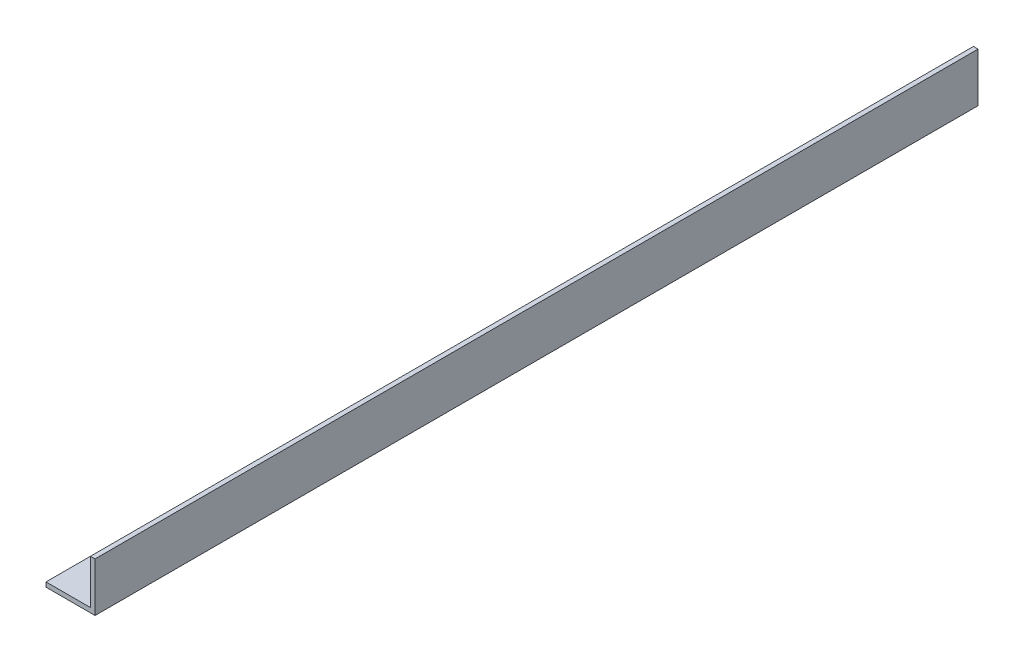
SolidWorks part; units mm, degrees
ref_plane "Front Plane" through (0, 0, 0) normal (0, 0, 1) x (1, 0, 0)
ref_plane "Top Plane" through (0, 0, 0) normal (0, 1, 0) x (1, 0, 0)
ref_plane "Right Plane" through (0, 0, 0) normal (1, 0, 0) x (0, 0, -1)
sketch "Sketch1" plane through (0, 0, 0) normal (0, 0, 1) x (1, 0, 0)
  line L0 (-12.7, 0) -> (0, 0)
  line L1 (0, 0) -> (0, 12.7)
  line L2 (0, 12.7) -> (-1.1906, 12.7)
  line L3 (-1.1906, 12.7) -> (-1.1906, 1.1906)
  line L4 (-1.1906, 1.1906) -> (-12.7, 1.1906)
  line L5 (-12.7, 0) -> (-12.7, 1.1906)
  line L6 (-0.5953, 12.7) -> (0, 12.7) construction
  line L7 (-12.7, 0.5953) -> (-12.7, 0) construction
  dimension "Vert" = 12.7
  dimension "Horz" = 12.7
  dimension "Thickness" = 1.1906
sketch "Sketch2" plane through (0, 0, 0) normal (1, 0, 0) x (0, 0, -1)
  line L0 (-114.3, 0) -> (114.3, 0) construction
  point P0 (-109.728, 0)
  point P4 (0, 0)
  point P5 (109.728, 0)
  dimension "Length" = 228.6
  dimension "D1" = 4.572
  dimension "D2" = 4.572
sketch "Sketch3" plane through (0, 0, 0) normal (0, 0, 1) x (1, 0, 0)
  line L0 (-12.7, 0) -> (0, 0) construction
  line L1 (0, 0) -> (0, 12.7) construction
  line L2 (0, 12.7) -> (-1.1906, 12.7) construction
  line L3 (-1.1906, 12.7) -> (-1.1906, 1.1906) construction
  line L4 (-1.1906, 1.1906) -> (-12.7, 1.1906) construction
  line L5 (-12.7, 0) -> (-12.7, 1.1906) construction
  line L6 (-12.7, 0) -> (0, 0)
  line L7 (0, 0) -> (0, 12.7)
  line L8 (0, 12.7) -> (-1.1906, 12.7)
  line L9 (-1.1906, 12.7) -> (-1.1906, 1.1906)
  line L10 (-1.1906, 1.1906) -> (-12.7, 1.1906)
  line L11 (-12.7, 0) -> (-12.7, 1.1906)
extrude "Boss-Extrude1" add sketch "Sketch3" along normal up to vertex (114.3 mm away) and the other way up to vertex (114.3 mm away) up to point (0, 0, 114.3) other way up to point (0, 0, -114.3)
equation "\"D1@Sketch2\"=\"Length@Sketch2\"*.02"
equation "\"D2@Sketch2\"=\"D1@Sketch2\""
